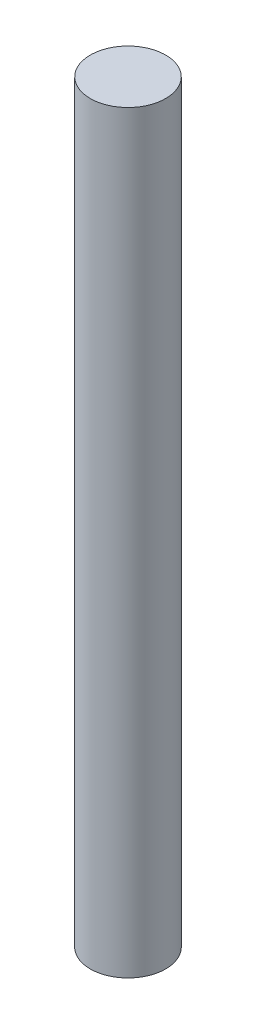
SolidWorks part; units mm, degrees
ref_plane "Alzado" through (0, 0, 0) normal (0, 0, 1) x (1, 0, 0)
ref_plane "Planta" through (0, 0, 0) normal (0, 1, 0) x (1, 0, 0)
ref_plane "Vista lateral" through (0, 0, 0) normal (1, 0, 0) x (0, 0, -1)
sketch "Croquis1" plane through (0, 0, 0) normal (0, 1, 0) x (1, 0, 0)
  circle A0 centre (0, 0) radius 0.5
  dimension "D1" = 1
extrude "Saliente-Extruir1" add sketch "Croquis1" along normal blind 10
